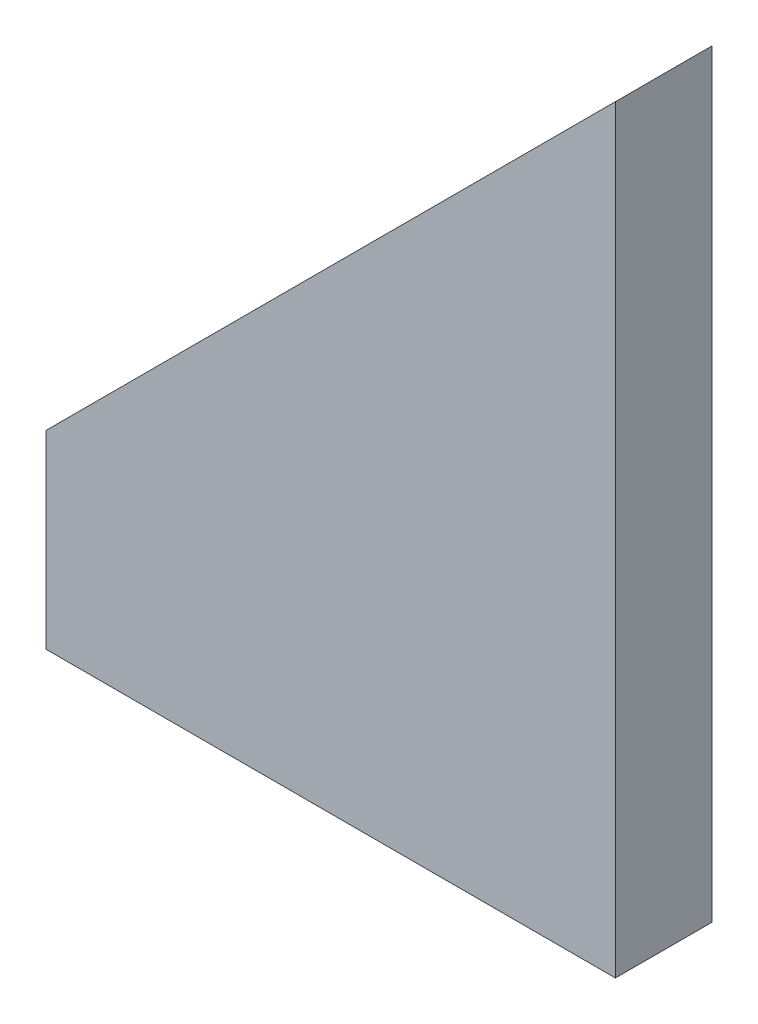
SolidWorks part; units mm, degrees
ref_plane "Front Plane" through (0, 0, 0) normal (0, 0, 1) x (1, 0, 0)
ref_plane "Top Plane" through (0, 0, 0) normal (0, 1, 0) x (1, 0, 0)
ref_plane "Right Plane" through (0, 0, 0) normal (1, 0, 0) x (0, 0, -1)
sketch "Sketch1" plane through (0, 0, 0) normal (0, 0, 1) x (1, 0, 0)
  line L0 (0, 0) -> (0, -100)
  line L1 (0, -100) -> (-75, -100)
  line L2 (-75, -75) -> (0, 0)
  line L3 (-75, -75) -> (-75, -100)
  point P3 (-116.8913, -100)
  dimension "D1" = 75
  dimension "D2" = 100
  dimension "D3" = 45
extrude "Boss-Extrude1" add sketch "Sketch1" along normal mid plane 12.7
